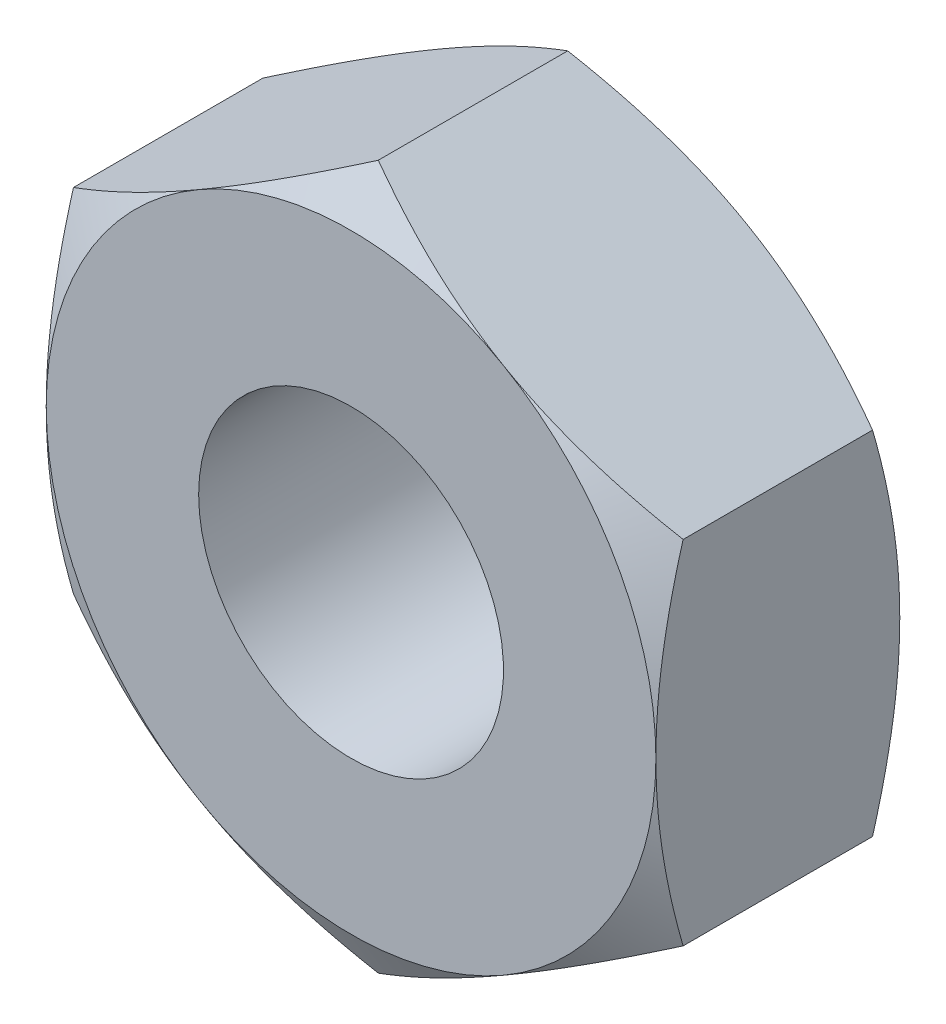
SolidWorks part; units mm, degrees
ref_plane "Front" through (0, 0, 0) normal (0, 0, 1) x (1, 0, 0)
ref_plane "Top" through (0, 0, 0) normal (0, 1, 0) x (1, 0, 0)
ref_plane "Right" through (0, 0, 0) normal (1, 0, 0) x (0, 0, -1)
sketch "Sketch1" plane through (0, 0, 0) normal (0, 0, 1) x (1, 0, 0)
  line L1 (-2, 1.1547) -> (-2, -1.1547)
  line L2 (-2, -1.1547) -> (0, -2.3094)
  line L3 (0, -2.3094) -> (2, -1.1547)
  line L4 (2, -1.1547) -> (2, 1.1547)
  line L5 (2, 1.1547) -> (0, 2.3094)
  line L6 (0, 2.3094) -> (-2, 1.1547)
  circle A0 centre (0, 0) radius 2 construction
  circle A1 centre (0, 0) radius 1 construction
  point P10 (0, 1)
  dimension "hex" = 4
  dimension "dia" = 2
extrude "Extrude1" add sketch "Sketch1" along normal mid plane 1.6
sketch "Sketch10" plane through (0, 0, 0.8) normal (0, 0, 1) x (1, 0, 0)
  circle A0 centre (0, 0) radius 1 construction
  circle A1 centre (0, 0) radius 1
extrude "Cut-Extrude2" cut sketch "Sketch10" against normal through all draft 45
sketch "Sketch11" plane through (0, 0, -0.8) normal (0, 0, -1) x (-1, 0, 0)
  circle A0 centre (0, 0) radius 1 construction
  circle A1 centre (0, 0) radius 1
extrude "Cut-Extrude3" cut sketch "Sketch11" against normal through all draft 45
sketch "Sketch13" plane through (0, 0, -0.8) normal (0, 0, -1) x (-1, 0, 0)
  circle A0 centre (0, 0) radius 1 construction
  circle A1 centre (0, 0) radius 1
extrude "Boss-Extrude1" add sketch "Sketch13" against normal up to vertex (1.6 mm away) separate body up to point (-2, 1.1547, 0.8)
combine bodies "Combine1" operation type subtract main body 116 bodies to subtract 117
sketch "Sketch7" plane through (0, 0, 0.8) normal (0, 0, 1) x (1, 0, 0)
  circle A0 centre (0, 0) radius 2 construction
  circle A1 centre (0, 0) radius 2
extrude "Extrude2" cut sketch "Sketch7" against normal blind 25.4 draft 60 flip side to cut
mirror "Mirror2" about plane through (0, 0, 0) normal (0, 0, 1) of "Extrude2"
